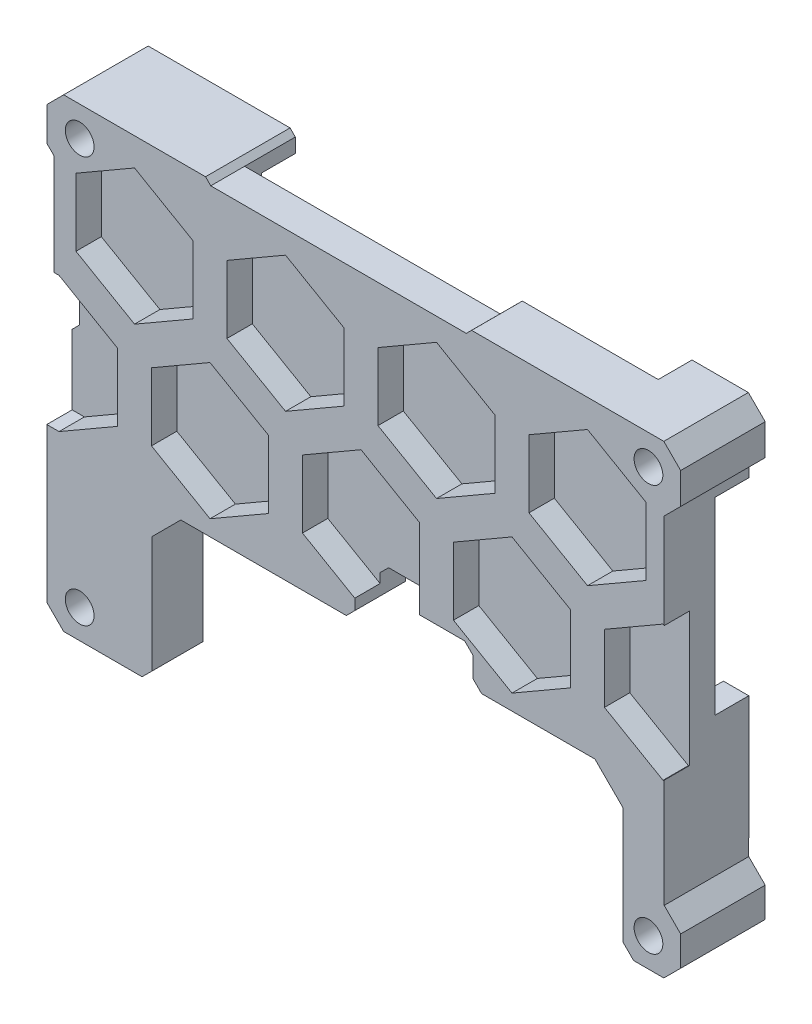
SolidWorks part; units mm, degrees
ref_plane "前视基准面" through (0, 0, 0) normal (0, 0, 1) x (1, 0, 0)
ref_plane "上视基准面" through (0, 0, 0) normal (0, 1, 0) x (1, 0, 0)
ref_plane "右视基准面" through (0, 0, 0) normal (1, 0, 0) x (0, 0, -1)
other "Configuration Table"
sketch "草图1" plane through (0, 0, 0) normal (0, 0, 1) x (1, 0, 0)
  line L1 (0, 0) -> (85, 0)
  line L2 (0, 0) -> (0, 65)
  line L3 (0, 65) -> (85, 65)
  line L4 (85, 0) -> (85, 65)
  dimension "D1" = 65
  dimension "D2" = 85
extrude "凸台-拉伸1" add sketch "草图1" along normal blind 10
sketch "草图2" plane through (0, 0, 0) normal (0, 0, -1) x (-1, 0, 0)
  circle A0 centre (-76.1669, 56.4425) radius 1.7
  circle A1 centre (-8.8888, 56.4425) radius 1.7
  circle A2 centre (-76.1669, 8.4151) radius 1.7
  circle A3 centre (-8.8888, 8.4151) radius 1.7
extrude "切除-拉伸1" cut sketch "草图2" against normal up to next
sketch "草图3" plane through (0, 0, 0) normal (0, 0, -1) x (-1, 0, 0)
  line L28 (-85, 0) -> (-85, 65) construction
  line L29 (-85, 65) -> (0, 65)
  line L30 (-85, 65) -> (-85, 0)
  line L31 (-85, 0) -> (0, 0)
  line L32 (0, 65) -> (0, 0)
  line L56 (-5, 33.4629) -> (-5.8713, 34.3342)
  line L57 (-5, 6.9926) -> (-5, 33.4629)
  line L58 (-6.9926, 5) -> (-5, 6.9926)
  line L59 (-16.2697, 5) -> (-6.9926, 5)
  line L60 (-17.4616, 6.1866) -> (-16.2697, 5)
  line L61 (-31.7436, 6.1829) -> (-17.4616, 6.1866)
  line L62 (-32.9265, 5) -> (-31.7436, 6.1829)
  line L63 (-58.7727, 5) -> (-32.9265, 5)
  line L64 (-60.0435, 6.2655) -> (-58.7727, 5)
  line L65 (-73.1524, 6.2618) -> (-60.0435, 6.2655)
  line L66 (-74.4142, 5) -> (-73.1524, 6.2618)
  line L67 (-77.9822, 5) -> (-74.4142, 5)
  line L68 (-79.9747, 6.9926) -> (-77.9822, 5)
  line L69 (-79.9747, 10.5083) -> (-79.9747, 6.9926)
  line L70 (-78.0283, 12.46) -> (-79.9747, 10.5083)
  line L71 (-78.032, 52.3531) -> (-78.0283, 12.46)
  line L72 (-79.9747, 54.2958) -> (-78.032, 52.3531)
  line L73 (-79.9747, 57.9821) -> (-79.9747, 54.2958)
  line L74 (-77.9822, 59.9747) -> (-79.9747, 57.9821)
  line L75 (-55.2451, 59.9747) -> (-77.9822, 59.9747)
  line L76 (-54.6148, 59.3497) -> (-55.2451, 59.9747)
  line L77 (-24.3949, 59.3534) -> (-54.6148, 59.3497)
  line L78 (-23.7736, 59.9747) -> (-24.3949, 59.3534)
  line L79 (-6.9926, 59.9747) -> (-23.7736, 59.9747)
  line L80 (-5, 57.9821) -> (-6.9926, 59.9747)
  line L81 (-5, 54.0174) -> (-5, 57.9821)
  line L82 (-5.875, 53.1371) -> (-5, 54.0174)
  line L83 (-5.8713, 34.3342) -> (-5.875, 53.1371)
extrude "切除-拉伸2" cut sketch "草图3" against normal up to next
sketch "草图4" plane through (0, 0, 0) normal (0, 0, -1) x (-1, 0, 0)
  line L0 (-73.1524, 6.2618) -> (-73.1524, 20.0323)
  line L1 (-73.1524, 20.0323) -> (-69.8316, 23.3532)
  line L2 (-69.8316, 23.3532) -> (-46.788, 23.3532)
  line L3 (-46.788, 23.3532) -> (-20.8513, 23.3532)
  line L4 (-20.8513, 23.3532) -> (-17.4616, 19.9634)
  line L5 (-17.4616, 19.9634) -> (-17.4616, 6.1866)
  line L6 (-31.7436, 6.1829) -> (-17.4616, 6.1866) construction
  line L7 (-17.4616, 6.1866) -> (-17.4616, 0.194)
  line L8 (-17.4616, 0.194) -> (-73.1524, 0.194)
  line L9 (-73.1524, 0.194) -> (-73.1524, 6.2618)
  line L10 (-73.1524, 6.2618) -> (-60.0435, 6.2655) construction
  point P4 (-15.5571, 6.1866)
  point P12 (-17.4616, 6.1866)
  point P13 (-73.1524, 6.2618)
  dimension "D1" = 135
  dimension "D2" = 135
extrude "切除-拉伸4" cut sketch "草图4" against normal up to next
sketch "草图5" plane through (0, 0, 0) normal (0, 0, -1) x (-1, 0, 0)
  line L0 (-24.3949, 59.3534) -> (-24.3949, 53.9064)
  line L1 (-24.3949, 53.9064) -> (-25.5261, 52.7749)
  line L2 (-25.5261, 52.7749) -> (-53.4826, 52.7749)
  line L3 (-53.4826, 52.7749) -> (-54.6142, 53.9061)
  line L4 (-54.6142, 53.9061) -> (-54.6148, 59.3497)
  line L5 (-24.3949, 59.3534) -> (-54.6148, 59.3497) construction
  line L6 (-23.7736, 59.9747) -> (-24.3949, 59.3534) construction
  line L7 (-24.3949, 59.3534) -> (-54.6148, 59.3497)
  dimension "D1" = 135
  dimension "D2" = 134.993
  dimension "D3" = 1.6
  dimension "D4" = 1.6
extrude "切除-拉伸7" cut sketch "草图5" against normal blind 6
sketch "草图6" plane through (0, 0, 0) normal (0, 0, -1) x (-1, 0, 0)
  line L0 (-5.8713, 34.3342) -> (-11.1362, 34.3342)
  line L1 (-5, 33.4629) -> (-5.8713, 34.3342) construction
  line L2 (-11.1362, 34.3342) -> (-11.6877, 35.8362)
  line L3 (-11.6877, 35.8362) -> (-11.6877, 43.8362)
  line L4 (-11.6877, 43.8362) -> (-10.2735, 45.2504)
  line L5 (-10.2735, 45.2504) -> (-5.8735, 45.2504)
  line L6 (-5.8713, 34.3342) -> (-5.875, 53.1371) construction
  line L8 (-5.8735, 45.2504) -> (-5.8713, 34.3342)
  dimension "D1" = 4.4
  dimension "D2" = 135
  dimension "D3" = 159.838
  dimension "D4" = 1.6
  dimension "D5" = 2
  dimension "D6" = 8
extrude "切除-拉伸8" cut sketch "草图6" against normal blind 6
sketch "草图7" plane through (0, 0, 0) normal (0, 0, -1) x (-1, 0, 0)
  line L0 (-76.4321, 51.2623) -> (-74.4321, 51.2623)
  line L1 (-74.4321, 51.2623) -> (-71.3195, 54.3749)
  line L2 (-71.3195, 54.3749) -> (-71.3195, 58.3749)
  line L3 (-71.3195, 58.3749) -> (-71.3195, 59.9747)
  line L4 (-76.4321, 51.2623) -> (-78.0319, 51.2623)
  line L5 (-78.0298, 28.9377) -> (-75.0298, 28.9377)
  line L6 (-75.0298, 28.9377) -> (-75.0298, 13.9377)
  line L7 (-72.9158, 11.8236) -> (-75.0298, 13.9377)
  line L8 (-24.3949, 57.6633) -> (-23.7321, 57.6633)
  line L9 (-23.7321, 57.6633) -> (-23.0617, 58.334)
  line L10 (-23.0617, 58.334) -> (-12.072, 58.334)
  line L11 (-12.072, 58.334) -> (-12.072, 55.334)
  line L12 (-12.072, 55.334) -> (-9.875, 53.1371)
  line L13 (-9.875, 53.1371) -> (-5.875, 53.1371)
  line L14 (-6.5998, 12.014) -> (-10.5998, 12.014)
  line L15 (-10.5998, 12.014) -> (-12.014, 10.5998)
  line L16 (-12.014, 10.5998) -> (-12.014, 5)
  line L17 (-6.5998, 12.014) -> (-5, 12.014)
  line L18 (-72.9158, 11.8236) -> (-73.1524, 12.0603)
  line L37 (-5.8713, 34.3342) -> (-11.1362, 34.3342)
  line L38 (-11.1362, 34.3342) -> (-11.6877, 35.8362)
  line L39 (-11.6877, 35.8362) -> (-11.6877, 43.8362)
  line L40 (-11.6877, 43.8362) -> (-10.2735, 45.2504)
  line L41 (-10.2735, 45.2504) -> (-5.8735, 45.2504)
  line L42 (-5.8735, 45.2504) -> (-5.875, 53.1371)
  line L43 (-5.875, 53.1371) -> (-5, 54.0174)
  line L44 (-5, 54.0174) -> (-5, 57.9821)
  line L45 (-5, 57.9821) -> (-6.9926, 59.9747)
  line L46 (-6.9926, 59.9747) -> (-23.7736, 59.9747)
  line L47 (-23.7736, 59.9747) -> (-24.3949, 59.3534)
  line L48 (-24.3949, 59.3534) -> (-24.3949, 53.9064)
  line L49 (-24.3949, 53.9064) -> (-25.5261, 52.7749)
  line L50 (-25.5261, 52.7749) -> (-53.4826, 52.7749)
  line L51 (-53.4826, 52.7749) -> (-54.6142, 53.9061)
  line L52 (-54.6142, 53.9061) -> (-54.6148, 59.3497)
  line L53 (-54.6148, 59.3497) -> (-55.2451, 59.9747)
  line L54 (-55.2451, 59.9747) -> (-77.9822, 59.9747)
  line L55 (-77.9822, 59.9747) -> (-79.9747, 57.9821)
  line L56 (-79.9747, 57.9821) -> (-79.9747, 54.2958)
  line L57 (-79.9747, 54.2958) -> (-78.032, 52.3531)
  line L58 (-78.032, 52.3531) -> (-78.0283, 12.46)
  line L59 (-78.0283, 12.46) -> (-79.9747, 10.5083)
  line L60 (-79.9747, 10.5083) -> (-79.9747, 6.9926)
  line L61 (-79.9747, 6.9926) -> (-77.9822, 5)
  line L62 (-77.9822, 5) -> (-74.4142, 5)
  line L63 (-74.4142, 5) -> (-73.1524, 6.2618)
  line L64 (-73.1524, 6.2618) -> (-73.1524, 20.0323)
  line L65 (-73.1524, 20.0323) -> (-69.8316, 23.3532)
  line L66 (-69.8316, 23.3532) -> (-20.8513, 23.3532)
  line L67 (-20.8513, 23.3532) -> (-17.4616, 19.9634)
  line L68 (-17.4616, 19.9634) -> (-17.4616, 6.1866)
  line L69 (-17.4616, 6.1866) -> (-16.2697, 5)
  line L70 (-16.2697, 5) -> (-6.9926, 5)
  line L71 (-6.9926, 5) -> (-5, 6.9926)
  line L72 (-5, 6.9926) -> (-5, 33.4629)
  line L73 (-5, 33.4629) -> (-5.8713, 34.3342)
  line L74 (-5.8713, 34.3342) -> (-11.1362, 34.3342)
  line L75 (-11.1362, 34.3342) -> (-11.6877, 35.8362)
  line L76 (-11.6877, 35.8362) -> (-11.6877, 43.8362)
  line L77 (-11.6877, 43.8362) -> (-10.2735, 45.2504)
  line L78 (-10.2735, 45.2504) -> (-5.8735, 45.2504)
  line L79 (-5.8735, 45.2504) -> (-5.875, 53.1371)
  line L80 (-5.875, 53.1371) -> (-5, 54.0174)
  line L81 (-5, 54.0174) -> (-5, 57.9821)
  line L82 (-5, 57.9821) -> (-6.9926, 59.9747)
  line L83 (-6.9926, 59.9747) -> (-23.7736, 59.9747)
  line L84 (-23.7736, 59.9747) -> (-24.3949, 59.3534)
  line L85 (-24.3949, 59.3534) -> (-24.3949, 53.9064)
  line L86 (-24.3949, 53.9064) -> (-25.5261, 52.7749)
  line L87 (-25.5261, 52.7749) -> (-53.4826, 52.7749)
  line L88 (-53.4826, 52.7749) -> (-54.6142, 53.9061)
  line L89 (-54.6142, 53.9061) -> (-54.6148, 59.3497)
  line L90 (-54.6148, 59.3497) -> (-55.2451, 59.9747)
  line L91 (-55.2451, 59.9747) -> (-77.9822, 59.9747)
  line L92 (-77.9822, 59.9747) -> (-79.9747, 57.9821)
  line L93 (-79.9747, 57.9821) -> (-79.9747, 54.2958)
  line L94 (-79.9747, 54.2958) -> (-78.032, 52.3531)
  line L95 (-78.032, 52.3531) -> (-78.0283, 12.46)
  line L96 (-78.0283, 12.46) -> (-79.9747, 10.5083)
  line L97 (-79.9747, 10.5083) -> (-79.9747, 6.9926)
  line L98 (-79.9747, 6.9926) -> (-77.9822, 5)
  line L99 (-77.9822, 5) -> (-74.4142, 5)
  line L100 (-74.4142, 5) -> (-73.1524, 6.2618)
  line L101 (-73.1524, 6.2618) -> (-73.1524, 20.0323)
  line L102 (-73.1524, 20.0323) -> (-69.8316, 23.3532)
  line L103 (-69.8316, 23.3532) -> (-20.8513, 23.3532)
  line L104 (-20.8513, 23.3532) -> (-17.4616, 19.9634)
  line L105 (-17.4616, 19.9634) -> (-17.4616, 6.1866)
  line L106 (-17.4616, 6.1866) -> (-16.2697, 5)
  line L107 (-16.2697, 5) -> (-6.9926, 5)
  line L108 (-6.9926, 5) -> (-5, 6.9926)
  line L109 (-5, 6.9926) -> (-5, 33.4629)
  line L110 (-5, 33.4629) -> (-5.8713, 34.3342)
  line M51 (-5.8713, 34.3342) -> (-11.1362, 34.3342)
  line M52 (-11.1362, 34.3342) -> (-11.6877, 35.8362)
  line M53 (-11.6877, 35.8362) -> (-11.6877, 43.8362)
  line M54 (-11.6877, 43.8362) -> (-10.2735, 45.2504)
  line M55 (-10.2735, 45.2504) -> (-5.8735, 45.2504)
  line M56 (-5.8735, 45.2504) -> (-5.875, 53.1371)
  line M62 (-24.3949, 59.3534) -> (-24.3949, 53.9064)
  line M63 (-24.3949, 53.9064) -> (-25.5261, 52.7749)
  line M64 (-25.5261, 52.7749) -> (-53.4826, 52.7749)
  line M65 (-53.4826, 52.7749) -> (-54.6142, 53.9061)
  line M66 (-54.6142, 53.9061) -> (-54.6148, 59.3497)
  line M67 (-54.6148, 59.3497) -> (-55.2451, 59.9747)
  line M68 (-55.2451, 59.9747) -> (-77.9822, 59.9747)
  line M72 (-78.032, 52.3531) -> (-78.0283, 12.46)
  line M78 (-73.1524, 6.2618) -> (-73.1524, 20.0323)
  line M79 (-73.1524, 20.0323) -> (-69.8316, 23.3532)
  line M80 (-69.8316, 23.3532) -> (-20.8513, 23.3532)
  line M81 (-20.8513, 23.3532) -> (-17.4616, 19.9634)
  line M82 (-17.4616, 19.9634) -> (-17.4616, 6.1866)
  line M83 (-17.4616, 6.1866) -> (-16.2697, 5)
  line M84 (-16.2697, 5) -> (-6.9926, 5)
  line M86 (-5, 6.9926) -> (-5, 33.4629)
  line M87 (-5, 33.4629) -> (-5.8713, 34.3342)
  dimension "D2" = 90
  dimension "D3" = 15
  dimension "D4" = 135
  dimension "D5" = 4
  dimension "D6" = 3
  dimension "D7" = 135
  dimension "D8" = 45
  dimension "D9" = 3
  dimension "D1" = 0
extrude "切除-拉伸11" cut sketch "草图7" against normal blind 4 contours L14 L17 L13 L12 L11 L10 L9 L8 L3 L2 L1 L0 L4 L5 L6 L7 L16 L15 M86 M87 M51 M52 M53 M54 M55 M56 M62 M63 M64 M65 M66 M67 M68 M72 M78 M79 M80 M81 M82 M83 M84
sketch "草图8" plane through (0, 0, 4) normal (0, 0, -1) x (-1, 0, 0)
  line L1 (-73.3481, 45.9587) -> (-65.3481, 45.9587)
  line L2 (-73.3481, 45.9587) -> (-73.3481, 40.9587)
  line L3 (-73.3481, 40.9587) -> (-65.3481, 40.9587)
  line L4 (-65.3481, 45.9587) -> (-65.3481, 40.9587)
  point P4 (0, 0)
  dimension "D1" = 5
  dimension "D2" = 8
extrude "切除-拉伸12" cut sketch "草图8" against normal blind 1
sketch "草图10" plane through (0, 0, 4) normal (0, 0, -1) x (-1, 0, 0)
  line L0 (-41.5465, 34.8898) -> (-37.5465, 34.8898)
  line L1 (-46.9465, 34.8898) -> (-41.5465, 34.8898)
  line L2 (-46.9465, 34.8898) -> (-46.9465, 28.8898)
  line L3 (-46.9465, 28.8898) -> (-41.5465, 28.8898)
  line L4 (-41.5465, 34.8898) -> (-41.5465, 28.8898)
  line L5 (-37.5465, 34.8898) -> (-32.1465, 34.8898)
  line L6 (-37.5465, 34.8898) -> (-37.5465, 28.8898)
  line L7 (-37.5465, 28.8898) -> (-32.1465, 28.8898)
  line L8 (-32.1465, 34.8898) -> (-32.1465, 28.8898)
  line L9 (-37.5465, 28.8898) -> (-41.5465, 28.8898)
  dimension "D1" = 5.4
  dimension "D2" = 6
  dimension "D3" = 5.4
  dimension "D4" = 4
extrude "凸台-拉伸2" add sketch "草图10" along normal up to vertex (3.04 mm away) contours L4 L1 L2 L3 | L9 L6 L0 L4 | L8 L5 L6 L7
sketch "草图11" plane through (0, 0, 4) normal (0, 0, -1) x (-1, 0, 0)
  line L1 (-40.8318, 43.6929) -> (-36.6318, 43.6929)
  line L2 (-40.8318, 43.6929) -> (-40.8318, 38.6929)
  line L3 (-40.8318, 38.6929) -> (-36.6318, 38.6929)
  line L4 (-36.6318, 43.6929) -> (-36.6318, 38.6929)
  point P4 (0, 0)
  dimension "D1" = 4.2
  dimension "D2" = 5
extrude "凸台-拉伸3" add sketch "草图11" along normal up to vertex (2.3001 mm away)
sketch "草图12" plane through (0, 0, 4) normal (0, 0, -1) x (-1, 0, 0)
  line L1 (-30.6106, 30.6859) -> (-18.6106, 30.6859)
  line L2 (-30.6106, 30.6859) -> (-30.6106, 24.6859)
  line L3 (-30.6106, 24.6859) -> (-18.6106, 24.6859)
  line L4 (-18.6106, 30.6859) -> (-18.6106, 24.6859)
  dimension "D1" = 12
  dimension "D2" = 6
extrude "凸台-拉伸4" add sketch "草图12" along normal up to vertex (2.89 mm away)
sketch "草图13" plane through (0, 0, 4) normal (0, 0, -1) x (-1, 0, 0)
  line L1 (-64.5698, 40.6188) -> (-58.0698, 40.6188)
  line L2 (-64.5698, 40.6188) -> (-64.5698, 35.5033)
  line L3 (-64.5698, 35.5033) -> (-58.0698, 35.5033)
  line L4 (-58.0698, 40.6188) -> (-58.0698, 35.5033)
  point P4 (-58.0698, 40.6188)
extrude "凸台-拉伸5" add sketch "草图13" along normal offset from surface (3.6 mm away) 0.4
sketch "草图14" plane through (0, 0, 4) normal (0, 0, -1) x (-1, 0, 0)
  line L1 (-65.7408, 30.6119) -> (-59.7408, 30.6119)
  line L2 (-65.7408, 30.6119) -> (-65.7408, 23.6119)
  line L3 (-65.7408, 23.6119) -> (-59.7408, 23.6119)
  line L4 (-59.7408, 30.6119) -> (-59.7408, 23.6119)
  dimension "D1" = 7
  dimension "D2" = 6
extrude "凸台-拉伸6" add sketch "草图14" along normal up to vertex (2.89 mm away)
sketch "草图15" plane through (0, 0, 10) normal (0, 0, 1) x (1, 0, 0)
  line L0 (69.8316, 23.3532) -> (20.8513, 23.3532) construction
  line L1 (41.4288, 23.3532) -> (55.4288, 23.3532)
  line L2 (41.4288, 23.3532) -> (41.4288, 27.7532)
  line L3 (41.4288, 27.7532) -> (55.4288, 27.7532)
  line L4 (55.4288, 23.3532) -> (55.4288, 27.7532)
  dimension "D1" = 14
  dimension "D2" = 4.4
extrude "切除-拉伸13" cut sketch "草图15" against normal up to surface (6 mm away) up to face at (69.3481, 43.4587, 4)
chamfer "倒角1" distance 1 angle 45 4 edges at (55.4288, 23.3532, 7) (55.4288, 27.7532, 7) (41.4288, 27.7532, 7) (41.4288, 23.3532, 7)
chamfer "倒角2" distance 0.6 angle 45 4 edges at (58.0698, 38.0611, 4) (61.3198, 40.6188, 4) (64.5698, 38.0611, 4) (61.3198, 35.5033, 4)
chamfer "倒角3" distance 0.6 angle 45 4 edges at (39.5465, 28.8898, 4) (32.1465, 31.8898, 4) (39.5465, 34.8898, 4) (46.9465, 31.8898, 4)
chamfer "倒角4" distance 0.6 angle 45 4 edges at (18.6106, 27.6859, 4) (24.6106, 24.6859, 4) (30.6106, 27.6859, 4) (24.6106, 30.6859, 4)
chamfer "倒角5" distance 0.6 angle 45 4 edges at (36.6318, 41.1929, 4) (38.7318, 38.6929, 4) (40.8318, 41.1929, 4) (38.7318, 43.6929, 4)
chamfer "倒角6" distance 0.6 angle 45 3 edges at (59.7408, 27.1119, 4) (62.7408, 30.6119, 4) (65.7408, 27.1119, 4)
sketch "草图17" plane through (0, 0, 10) normal (0, 0, 1) x (1, 0, 0)
  line L0 (40.1661, 44.6744) -> (40.1661, 52.6744)
  line L1 (22.3061, 44.6744) -> (22.3061, 52.6744)
  line L2 (22.3061, 52.6744) -> (15.3779, 56.6744)
  line L3 (15.3779, 56.6744) -> (8.4497, 52.6744)
  line L4 (8.4497, 52.6744) -> (8.4497, 44.6744)
  line L5 (8.4497, 44.6744) -> (15.3779, 40.6744)
  line L6 (15.3779, 40.6744) -> (22.3061, 44.6744)
  line L7 (40.1661, 52.6744) -> (33.2379, 56.6744)
  line L8 (33.2379, 56.6744) -> (26.3097, 52.6744)
  line L9 (26.3097, 52.6744) -> (26.3097, 44.6744)
  line L10 (26.3097, 44.6744) -> (33.2379, 40.6744)
  line L11 (33.2379, 40.6744) -> (40.1661, 44.6744)
  line L12 (58.0261, 44.6744) -> (58.0261, 52.6744)
  line L13 (58.0261, 52.6744) -> (51.0979, 56.6744)
  line L14 (51.0979, 56.6744) -> (44.1697, 52.6744)
  line L15 (44.1697, 52.6744) -> (44.1697, 44.6744)
  line L16 (44.1697, 44.6744) -> (51.0979, 40.6744)
  line L17 (51.0979, 40.6744) -> (58.0261, 44.6744)
  line L18 (75.8861, 44.6744) -> (75.8861, 52.6744)
  line L19 (75.8861, 52.6744) -> (68.9579, 56.6744)
  line L20 (68.9579, 56.6744) -> (62.0297, 52.6744)
  line L21 (62.0297, 52.6744) -> (62.0297, 44.6744)
  line L22 (62.0297, 44.6744) -> (68.9579, 40.6744)
  line L23 (68.9579, 40.6744) -> (75.8861, 44.6744)
  line L24 (93.7461, 44.6744) -> (93.7461, 52.6744)
  line L25 (93.7461, 52.6744) -> (86.8179, 56.6744)
  line L26 (86.8179, 56.6744) -> (79.8897, 52.6744)
  line L27 (79.8897, 52.6744) -> (79.8897, 44.6744)
  line L28 (79.8897, 44.6744) -> (86.8179, 40.6744)
  line L29 (86.8179, 40.6744) -> (93.7461, 44.6744)
  line L30 (31.2361, 29.2072) -> (31.2361, 37.2072)
  line L31 (31.2361, 37.2072) -> (24.3079, 41.2072)
  line L32 (24.3079, 41.2072) -> (17.3797, 37.2072)
  line L33 (17.3797, 37.2072) -> (17.3797, 29.2072)
  line L34 (17.3797, 29.2072) -> (24.3079, 25.2072)
  line L35 (24.3079, 25.2072) -> (31.2361, 29.2072)
  line L36 (49.0961, 29.2072) -> (49.0961, 37.2072)
  line L37 (49.0961, 37.2072) -> (42.1679, 41.2072)
  line L38 (42.1679, 41.2072) -> (35.2397, 37.2072)
  line L39 (35.2397, 37.2072) -> (35.2397, 29.2072)
  line L40 (35.2397, 29.2072) -> (42.1679, 25.2072)
  line L41 (42.1679, 25.2072) -> (49.0961, 29.2072)
  line L42 (66.9561, 29.2072) -> (66.9561, 37.2072)
  line L43 (66.9561, 37.2072) -> (60.0279, 41.2072)
  line L44 (60.0279, 41.2072) -> (53.0997, 37.2072)
  line L45 (53.0997, 37.2072) -> (53.0997, 29.2072)
  line L46 (53.0997, 29.2072) -> (60.0279, 25.2072)
  line L47 (60.0279, 25.2072) -> (66.9561, 29.2072)
  line L48 (84.8161, 29.2072) -> (84.8161, 37.2072)
  line L49 (84.8161, 37.2072) -> (77.8879, 41.2072)
  line L50 (77.8879, 41.2072) -> (70.9597, 37.2072)
  line L51 (70.9597, 37.2072) -> (70.9597, 29.2072)
  line L52 (70.9597, 29.2072) -> (77.8879, 25.2072)
  line L53 (77.8879, 25.2072) -> (84.8161, 29.2072)
  line L54 (13.3761, 29.2072) -> (13.3761, 37.2072)
  line L55 (13.3761, 37.2072) -> (6.4479, 41.2072)
  line L56 (6.4479, 41.2072) -> (-0.4803, 37.2072)
  line L57 (-0.4803, 37.2072) -> (-0.4803, 29.2072)
  line L58 (-0.4803, 29.2072) -> (6.4479, 25.2072)
  line L59 (6.4479, 25.2072) -> (13.3761, 29.2072)
  circle A0 centre (15.3779, 48.6744) radius 6.9282 construction
  point P1 (15.3779, 48.6744)
  dimension "D1" = 8
  dimension "D2" = 5
  dimension "D3" = 2
extrude "切除-拉伸15" cut sketch "草图17" against normal blind 3
sketch "草图18" plane through (0, 0, 10) normal (0, 0, 1) x (1, 0, 0)
  line L0 (6.4479, 41.2072) -> (5.8727, 41.2072)
  line L1 (5.875, 53.1371) -> (5.8726, 40.875) construction
  line L2 (5.8727, 41.2072) -> (5.8726, 40.875)
  line L3 (5.8726, 40.875) -> (6.4479, 41.2072)
  line L4 (6.4479, 25.2072) -> (5, 25.2072)
  line L5 (5, 26.0431) -> (5, 6.9926) construction
  line L6 (5, 25.2072) -> (5, 26.0431)
  line L7 (5, 26.0431) -> (6.4479, 25.2072) construction
  line L8 (5, 26.0431) -> (6.4479, 25.2072)
  line L9 (49.0961, 29.2072) -> (49.0961, 27.7532)
  line L10 (54.4288, 27.7532) -> (46.5777, 27.7532) construction
  line L11 (49.0961, 27.7532) -> (46.5777, 27.7532)
  line L12 (46.5777, 27.7532) -> (49.0961, 29.2072)
extrude "切除-拉伸16" cut sketch "草图18" against normal blind 3
